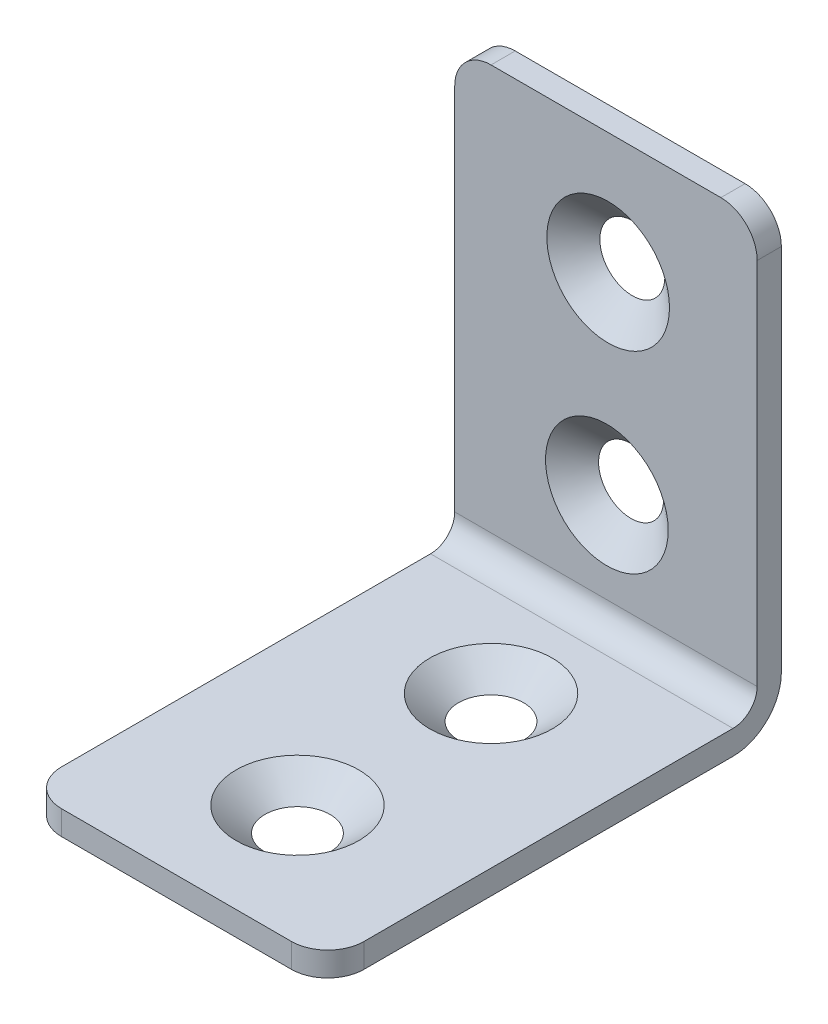
SolidWorks part; units mm, degrees
material "AISI 304"
ref_plane "Front Plane" through (0, 0, 0) normal (0, 0, 1) x (1, 0, 0)
ref_plane "Top Plane" through (0, 0, 0) normal (0, 1, 0) x (1, 0, 0)
ref_plane "Right Plane" through (0, 0, 0) normal (1, 0, 0) x (0, 0, -1)
sketch "Sketch1" plane through (0, 0, 0) normal (0, 0, 1) x (1, 0, 0)
  line L0 (0, 0) -> (31.75, 0)
  line L1 (31.75, 0) -> (31.75, 47.625)
  line L2 (31.75, 47.625) -> (0, 47.625)
  line L3 (0, 47.625) -> (0, 0)
  dimension "D1" = 31.75
  dimension "D2" = 47.625
extrude "Boss-Extrude1" add sketch "Sketch1" along normal blind 2.54
sketch "Sketch3" plane through (0, 0, 0) normal (0, -1, 0) x (1, 0, 0)
  line L0 (0, 2.54) -> (0, 47.625)
  line L1 (31.75, 2.54) -> (31.75, 47.625)
  line L2 (31.75, 47.625) -> (0, 47.625)
  line L3 (0, 2.54) -> (31.75, 2.54)
  dimension "D1" = 45.085
  dimension "D2" = 31.75
extrude "Boss-Extrude2" add sketch "Sketch3" against normal blind 2.54 contours L0 L2 L1 L3
fillet "Fillet1" radius 5.08 1 edges at (15.875, 0, 0)
fillet "Fillet2" radius 2.54 1 edges at (15.875, 2.54, 2.54)
fillet "Fillet3" radius 3.81 4 edges at (0, 1.27, 47.625) (31.75, 1.27, 47.625) (31.75, 47.625, 1.27) (0, 47.625, 1.27)
sketch "Sketch4" plane through (0, 0, 2.54) normal (0, 0, 1) x (1, 0, 0)
  line L0 (0, 0) -> (15.875, 0) construction
  line L1 (27.94, 0) -> (3.81, 0) construction
  line L2 (15.875, 0) -> (16.1904, 47.625) construction
  line L3 (27.94, 47.625) -> (3.81, 47.625) construction
  line L4 (16.1904, 47.625) -> (16.1063, 34.925) construction
  line L5 (16.1063, 34.925) -> (15.9717, 14.605) construction
  circle A0 centre (16.1063, 34.925) radius 3.175
  circle A1 centre (15.9717, 14.605) radius 3.175
  dimension "D5" = 6.35
  dimension "D6" = 6.35
  dimension "D1" = 15.875
  dimension "D2" = 47.625
  dimension "D3" = 12.7
  dimension "D4" = 20.32
hole_wizard "CSK for 1/4 Flat Head Machine Screw (100)1" positions "3DSketch1" profile "Sketch5" countersink size "1/4" standard "ANSI Inch" end condition through all
sketch3d "3DSketch1"
  point P0 (16.1063, 34.925, 2.54)
  point P3 (15.9717, 14.605, 2.54)
sketch "Sketch5" plane through (16.1063, 34.925, 2.54) normal (1, 0, 0) x (0, -1, 0)
  line L0 (0, 0) -> (0, 2.54)
  line L1 (0, 2.54) -> (3.3782, 2.54)
  line L2 (3.3782, 2.54) -> (3.3782, 2.5682)
  line L3 (3.3782, 2.5682) -> (6.4389, 0)
  line L5 (6.4389, 0) -> (0, 0)
  line L6 (-3.3782, 2.5682) -> (-6.4389, 0) construction
  line L11 (0, -6.35) -> (0, 107.95) construction
  dimension "Thru Hole Dia." = 6.7564
  dimension "Thru Hole Depth" = 2.54
  dimension "Near C'Sink Dia." = 12.8778
  dimension "Near C'Sink Angle" = 100
sketch "Sketch6" plane through (0, 2.54, 0) normal (0, 1, 0) x (1, 0, 0)
  line L0 (0, 0) -> (15.875, 0) construction
  line L1 (27.94, 0) -> (3.81, 0) construction
  line L2 (15.875, 0) -> (15.875, -47.625) construction
  line L3 (27.94, -47.625) -> (3.81, -47.625) construction
  line L4 (15.875, -47.625) -> (15.875, -34.925) construction
  line L5 (15.875, -34.925) -> (15.875, -14.605) construction
  dimension "D1" = 47.625
  dimension "D2" = 15.875
  dimension "D3" = 12.7
  dimension "D4" = 20.32
hole_wizard "CSK for 1/4 Flat Head Machine Screw (100)2" positions "3DSketch2" profile "Sketch7" countersink size "1/4" standard "ANSI Inch" end condition through all
sketch3d "3DSketch2"
  point P0 (15.875, 2.54, 34.925)
  point P3 (15.875, 2.54, 14.605)
sketch "Sketch7" plane through (15.875, 2.54, 34.925) normal (1, 0, 0) x (0, 0, 1)
  line L0 (0, 0) -> (0, 2.54)
  line L1 (0, 2.54) -> (3.3782, 2.54)
  line L2 (3.3782, 2.54) -> (3.3782, 2.5682)
  line L3 (3.3782, 2.5682) -> (6.4389, 0)
  line L5 (6.4389, 0) -> (0, 0)
  line L6 (-3.3782, 2.5682) -> (-6.4389, 0) construction
  line L11 (0, -6.35) -> (0, 107.95) construction
  dimension "Thru Hole Dia." = 6.7564
  dimension "Thru Hole Depth" = 2.54
  dimension "Near C'Sink Dia." = 12.8778
  dimension "Near C'Sink Angle" = 100
